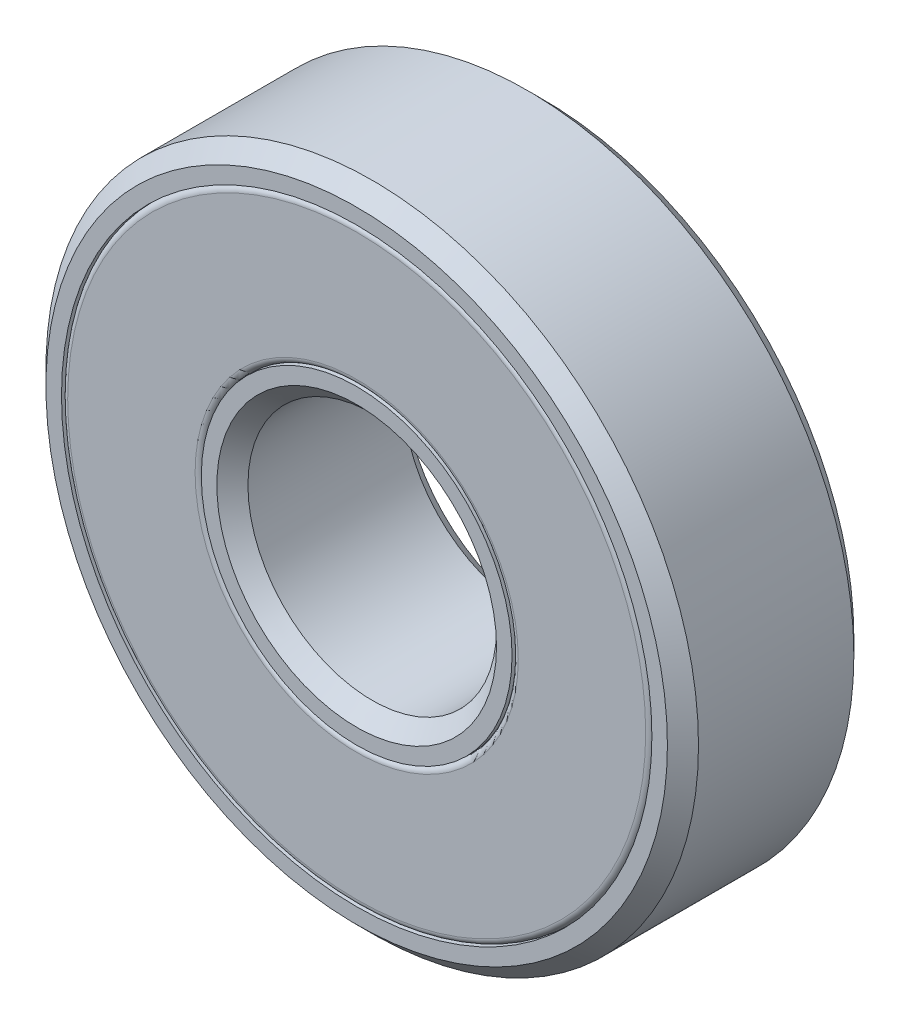
SolidWorks part; units mm, degrees
ref_plane "Front Plane" through (0, 0, 0) normal (0, 0, 1) x (1, 0, 0)
ref_plane "Top Plane" through (0, 0, 0) normal (0, 1, 0) x (1, 0, 0)
ref_plane "Right Plane" through (0, 0, 0) normal (1, 0, 0) x (0, 0, -1)
sketch "Sketch1" plane through (0, 0, 0) normal (0, 0, 1) x (1, 0, 0)
  circle A0 centre (0, 0) radius 4
  circle A1 centre (0, 0) radius 5
  circle A2 centre (0, 0) radius 10.5
  circle A3 centre (0, 0) radius 9.5
  dimension "D1" = 1
  dimension "D2" = 1
extrude "Boss-Extrude1" add sketch "Sketch1" along normal blind 6 contours A1 A0 | A2 A3
sketch "Sketch2" plane through (0, 0, 0) normal (0, 0, 1) x (1, 0, 0)
  circle A0 centre (0, 0) radius 9.5 construction
  circle A1 centre (0, 0) radius 5 construction
  circle A2 centre (0, 0) radius 9.5
  circle A3 centre (0, 0) radius 5
extrude "Boss-Extrude2" add sketch "Sketch2" along normal blind 6 separate body
chamfer "Chamfer1" distance 0.5 angle 45 2 edges at (10.5, 0, 6) (10.5, 0, 0)
chamfer "Chamfer2" distance 0.5 angle 45 2 edges at (4, 0, 6) (4, 0, 0)
fillet "Fillet1" radius 0.2 4 edges at (5, 0, 6) (9.5, 0, 6) (5, 0, 0) (9.5, 0, 0)
